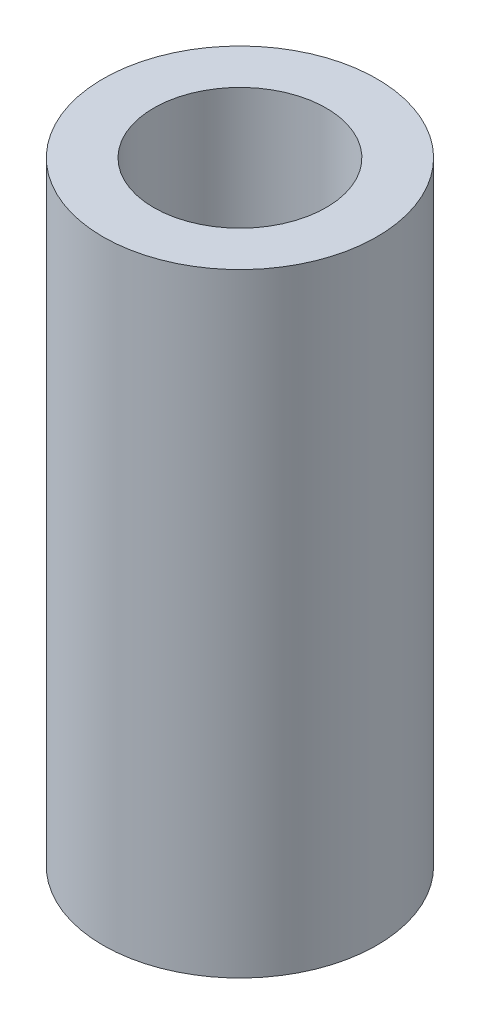
SolidWorks part; units mm, degrees
ref_plane "Front Plane" through (0, 0, 0) normal (0, 0, 1) x (1, 0, 0)
ref_plane "Top Plane" through (0, 0, 0) normal (0, 1, 0) x (1, 0, 0)
ref_plane "Right Plane" through (0, 0, 0) normal (1, 0, 0) x (0, 0, -1)
sketch "Sketch1" plane through (0, 0, 0) normal (0, 1, 0) x (1, 0, 0)
  circle A0 centre (0, 0) radius 6.35
  dimension "D1" = 12.7
extrude "Boss-Extrude1" add sketch "Sketch1" along normal blind 28.45
sketch "Sketch2" plane through (0, 28.45, 0) normal (0, 1, 0) x (1, 0, 0)
  circle A0 centre (0, 0) radius 4
  dimension "D1" = 8
sketch "Sketch3" plane through (0, 28.45, 0) normal (0, 1, 0) x (1, 0, 0)
  circle A0 centre (0, 0) radius 4
  dimension "D1" = 8
extrude "Cut-Extrude2" cut sketch "Sketch3" against normal through all
